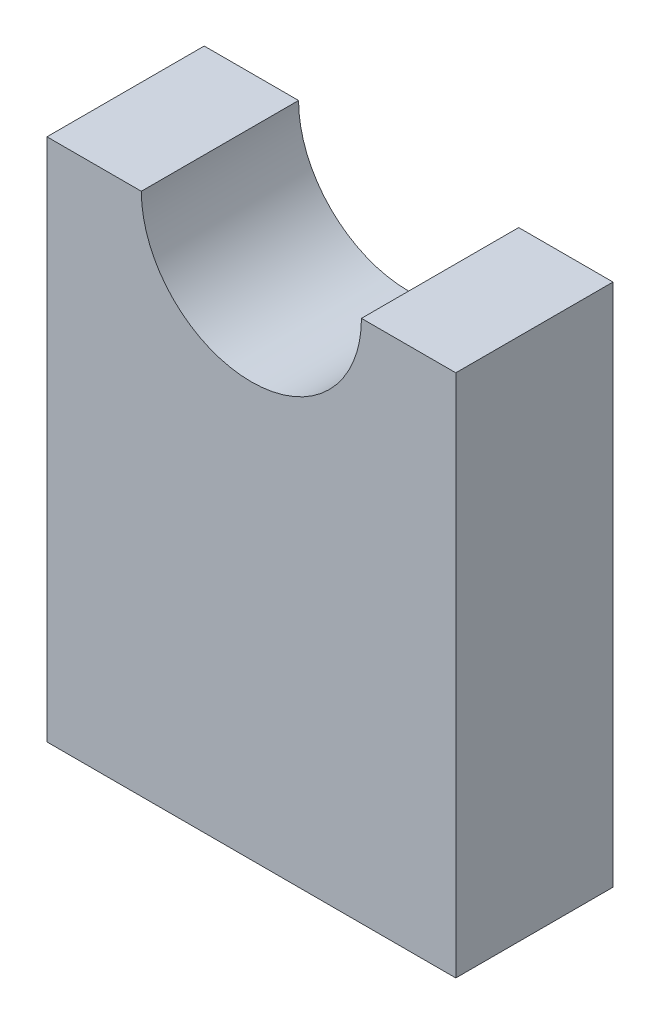
SolidWorks part; units mm, degrees
ref_plane "前视基准面" through (0, 0, 0) normal (0, 0, 1) x (1, 0, 0)
ref_plane "上视基准面" through (0, 0, 0) normal (0, 1, 0) x (1, 0, 0)
ref_plane "右视基准面" through (0, 0, 0) normal (1, 0, 0) x (0, 0, -1)
sketch "草图1" plane through (0, 0, 0) normal (0, 0, 1) x (1, 0, 0)
  line L0 (39, 107.5524) -> (39, -6.9581) construction
  line L1 (0, 0) -> (78, 0)
  line L2 (0, 0) -> (0, 100)
  line L3 (0, 100) -> (18, 100)
  line L4 (78, 0) -> (78, 100)
  line L5 (60, 100) -> (78, 100)
  arc A0 (18, 100) -> (60, 100) centre (39, 100) ccw
  dimension "D4" = 21
  dimension "D1" = 78
  dimension "D2" = 100
  dimension "D3" = 39
extrude "拉伸1" add sketch "草图1" along normal blind 30
